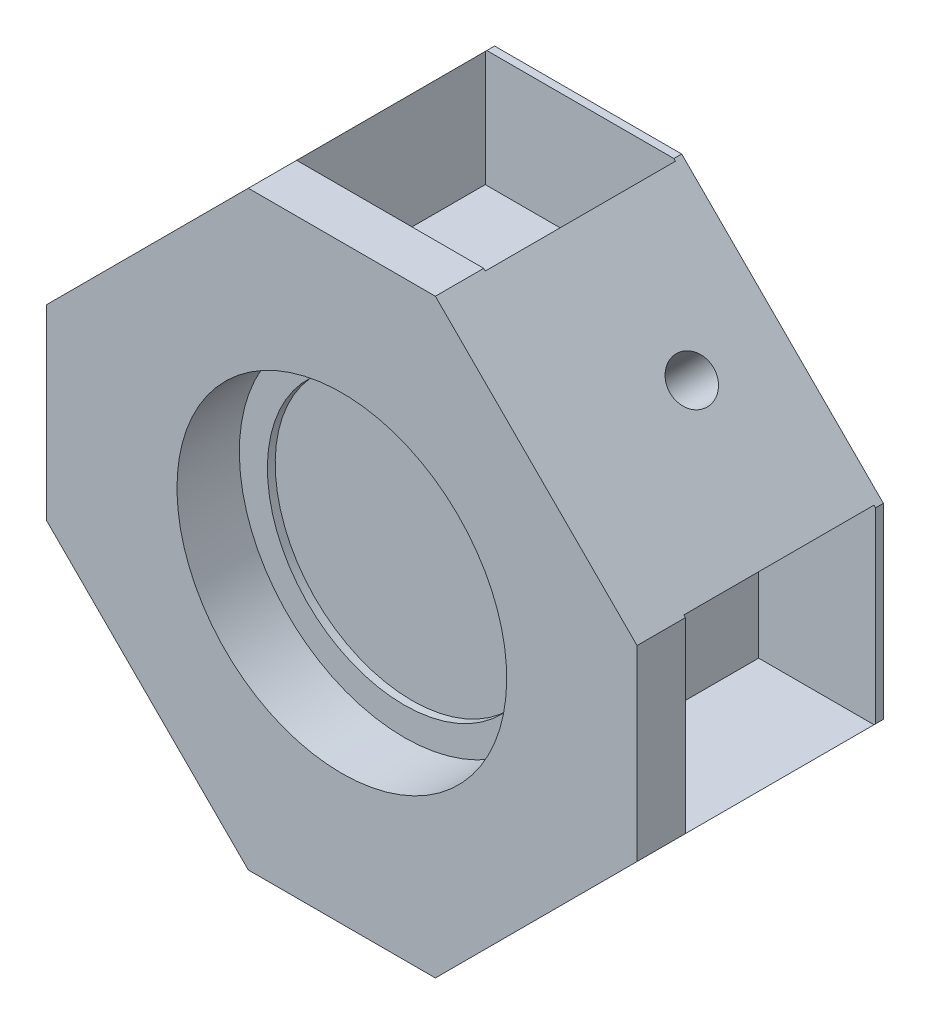
SolidWorks part; units mm, degrees
material "ABS"
ref_plane "Ebene vorne" through (0, 0, 0) normal (0, 0, 1) x (1, 0, 0)
ref_plane "Ebene oben" through (0, 0, 0) normal (0, 1, 0) x (1, 0, 0)
ref_plane "Ebene rechts" through (0, 0, 0) normal (1, 0, 0) x (0, 0, -1)
sketch "Skizze1" plane through (0, 0, 0) normal (0, 1, 0) x (1, 0, 0)
  line L0 (0, 0) -> (12, 0) construction
  line L1 (12, 0) -> (18.9367, 6.9367) construction
  line L2 (18.9367, 6.9367) -> (18.9367, 18.9367) construction
  line L3 (18.9367, 12.9367) -> (-12.2794, 12.9367) construction
  line L4 (12, 25.8734) -> (18.9367, 18.9367) construction
  line L5 (0, 25.8734) -> (12, 25.8734) construction
  line L6 (6, 0) -> (6, 25.8734) construction
  line L7 (0, 0) -> (-6.9367, 6.9367) construction
  line L8 (-6.9367, 6.9367) -> (-6.9367, 18.9367) construction
  line L9 (0, 25.8734) -> (-6.9367, 18.9367) construction
  line L10 (24.9367, 31.8734) -> (24.9367, -6)
  line L11 (24.9367, -6) -> (-12.9367, -6)
  line L12 (-12.9367, 31.8734) -> (-12.9367, -6)
  line L13 (24.9367, 31.8734) -> (-12.9367, 31.8734)
  point P18 (6, -6)
  point P19 (24.9367, 12.9367)
  point P20 (-12.9367, 12.9367)
  dimension "D1" = 12
  dimension "D2" = 135
  dimension "D3" = 9.81
  dimension "D4" = 12
  dimension "D5" = 6
  dimension "D6" = 6
extrude "Aufsatz-Linear austragen1" add sketch "Skizze1" along normal blind 20
sketch "Skizze2" plane through (0, 0, 0) normal (0, -1, 0) x (1, 0, 0)
  line L0 (6, 6) -> (6, -31.8734) construction
  line L3 (-12.9367, -12.9367) -> (24.9367, -12.9367) construction
  line L5 (24.9367, -31.8734) -> (-12.9367, -31.8734) construction
  line L6 (24.9367, 6) -> (24.9367, -31.8734) construction
  circle A0 centre (6, -12.9367) radius 10.575
  point P11 (6, -12.9367)
  dimension "D1" = 21.15
extrude "Schnitt-Linear austragen1" cut sketch "Skizze2" against normal blind 4
sketch "Skizze3" plane through (0, 0, 6) normal (0, 0, 1) x (1, 0, 0)
  line L0 (6, 0) -> (6, 20) construction
  line L3 (0, 3.2) -> (12, 3.2)
  line L4 (12, 3.2) -> (12, 15.2)
  line L5 (12, 15.2) -> (0, 15.2)
  line L6 (0, 3.2) -> (0, 15.2)
  line L7 (-12.9367, 0) -> (24.9367, 0) construction
  line L8 (-12.9367, 20) -> (24.9367, 20) construction
  point P11 (6, 15.2)
  point P12 (6, 3.2)
  dimension "D1" = 3.2
  dimension "D2" = 12
  dimension "D3" = 12
extrude "Schnitt-Linear austragen3" cut sketch "Skizze3" against normal blind 7.5 contours L5 L6 L3 L4
fillet "Verrundung1" radius 8 4 edges at (-12.9367, 10, -31.8734) (24.9367, 10, -31.8734) (24.9367, 10, 6) (-12.9367, 10, 6)
pattern_circular "Kreismuster1" count 4 over 360 about axis through (6, 0, -12.9367) along (0, 1, 0) of "Schnitt-Linear austragen3"
sketch "Skizze4" plane through (0, 4, 0) normal (0, -1, 0) x (1, 0, 0)
  circle A0 centre (6, -12.9367) radius 8.775
  circle A1 centre (6, -12.9367) radius 10.575 construction
  dimension "D1" = 1.8
extrude "Schnitt-Linear austragen4" cut sketch "Skizze4" against normal blind 0.5
move or copy body "Körper-Verschieben/Kopieren1" bodies to move or copy 106 copy no rotation origin (0, 10, -12.9367) rotation axis (-1, 0, 0) rotation angle 90
sketch "Skizze5" plane through (0, 0, -2.9367) normal (0, 0, 1) x (1, 0, 0)
  line L0 (0, 28.9367) -> (-12.9367, 16)
  line L1 (-4.9367, 28.9367) -> (16.9367, 28.9367) construction
  line L2 (-12.9367, 16) -> (-12.9367, 28.9367)
  line L3 (-12.9367, 28.9367) -> (0, 28.9367)
  line L4 (6, -8.9367) -> (6, 31.5737) construction
  line L5 (16.9367, -8.9367) -> (-4.9367, -8.9367) construction
  line L6 (24.9367, 10) -> (-21.788, 10) construction
  line L7 (24.9367, 20.9367) -> (24.9367, -0.9367) construction
  line L8 (24.9367, 16) -> (24.9367, 28.9367)
  line L9 (24.9367, 28.9367) -> (12, 28.9367)
  line L10 (12, 28.9367) -> (24.9367, 16)
  line L11 (12, -8.9367) -> (24.9367, 4)
  line L12 (24.9367, -8.9367) -> (12, -8.9367)
  line L13 (24.9367, 4) -> (24.9367, -8.9367)
  line L14 (-12.9367, -8.9367) -> (0, -8.9367)
  line L15 (-12.9367, 4) -> (-12.9367, -8.9367)
  line L16 (0, -8.9367) -> (-12.9367, 4)
extrude "Schnitt-Linear austragen5" cut sketch "Skizze5" against normal through all
sketch "Skizze6" plane through (-14.4684, 14.4684, 0) normal (-0.7071, 0.7071, 0) x (0.7071, 0.7071, 0)
  circle A0 centre (11.2842, 12.9367) radius 1.4
  dimension "D1" = 2.8
extrude "Schnitt-Linear austragen6" cut sketch "Skizze6" against normal blind 6 and the other way blind 10
pattern_circular "Kreismuster2" count 4 every 90 about axis through (6, 10, 0) along (0, 0, 1) of "Schnitt-Linear austragen6"
sketch "Skizze7" plane through (20.4684, 20.4684, 0) normal (0.7071, 0.7071, 0) x (0.7071, -0.7071, 0)
  line L4 (14.8045, 18.7367) -> (-20.8482, 18.7367)
  line L5 (14.8045, 22.9367) -> (14.8045, 18.1367) construction
  line L7 (-20.8482, 18.7367) -> (-20.8482, 28.1102)
  line L10 (-11.9761, 22.9367) -> (6.3192, 22.9367) construction
  line L11 (-12.2727, 18.1367) -> (8.1238, 18.1367) construction
  line L12 (-20.8482, 28.1102) -> (14.8045, 28.1102)
  line L13 (14.8045, 28.1102) -> (14.8045, 18.7367)
  dimension "D1" = 0.6
extrude "Schnitt-Linear austragen8" cut sketch "Skizze7" against normal through all
sketch "Skizze8" plane through (-12.9367, 0, 0) normal (-1, 0, 0) x (0, 0, 1)
  line L0 (-6.0367, 3.9) -> (-6.0367, 16.1)
  line L1 (-6.0367, 16.1) -> (-18.2367, 16.1)
  line L2 (-18.2367, 16.1) -> (-18.2367, 3.9)
  line L3 (-18.2367, 3.9) -> (-6.0367, 3.9)
  line L4 (-6.1367, 16) -> (-18.1367, 16) construction
  line L5 (-6.1367, 4) -> (-6.1367, 16) construction
  dimension "D1" = 12.2
  dimension "D2" = 0.1
  dimension "D3" = 0.1
extrude "Schnitt-Linear austragen9" cut sketch "Skizze8" against normal blind 7.5
pattern_circular "Kreismuster11" count 4 over 360 about axis through (6, 10, 0) along (0, 0, 1) of "Schnitt-Linear austragen9"
